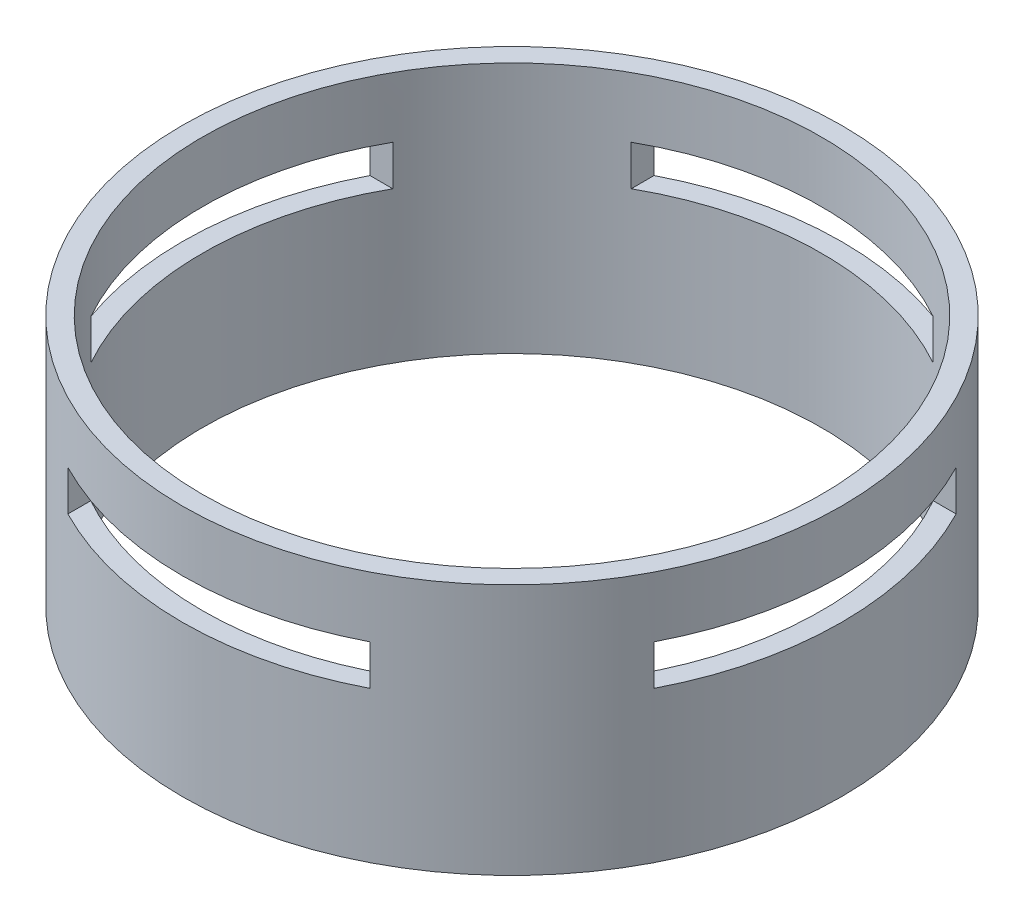
SolidWorks part; units mm, degrees
material "ABS"
ref_plane "Plan de face" through (0, 0, 0) normal (0, 0, 1) x (1, 0, 0)
ref_plane "Plan de dessus" through (0, 0, 0) normal (0, 1, 0) x (1, 0, 0)
ref_plane "Plan de droite" through (0, 0, 0) normal (1, 0, 0) x (0, 0, -1)
sketch "Esquisse1" plane through (0, 0, 0) normal (0, 1, 0) x (1, 0, 0)
  circle A0 centre (0, 0) radius 32.75
  circle A1 centre (0, 0) radius 30.75
  dimension "D1" = 65.5
  dimension "D2" = 2
extrude "Boss.-Extru.1" add sketch "Esquisse1" along normal blind 25
sketch "Esquisse2" plane through (0, 0, 0) normal (0, 0, 1) x (1, 0, 0)
  line L0 (0, 0) -> (0, 25) construction
  line L1 (-32.75, 0) -> (32.75, 0) construction
  line L2 (-15, 19) -> (15, 19)
  line L3 (-15, 19) -> (-15, 15)
  line L4 (-15, 15) -> (15, 15)
  line L5 (30.75, 25) -> (-30.75, 25) construction
  line L6 (15, 19) -> (15, 15)
  point P9 (0, 15)
  dimension "D1" = 4
  dimension "D2" = 30
  dimension "D3" = 15
extrude "Enlèv. mat.-Extru.1" cut sketch "Esquisse2" against normal through all
pattern_circular "Répétition circulaire1" count 4 every 90 about axis through (0, 0, 0) along (0, 1, 0) of "Enlèv. mat.-Extru.1"
